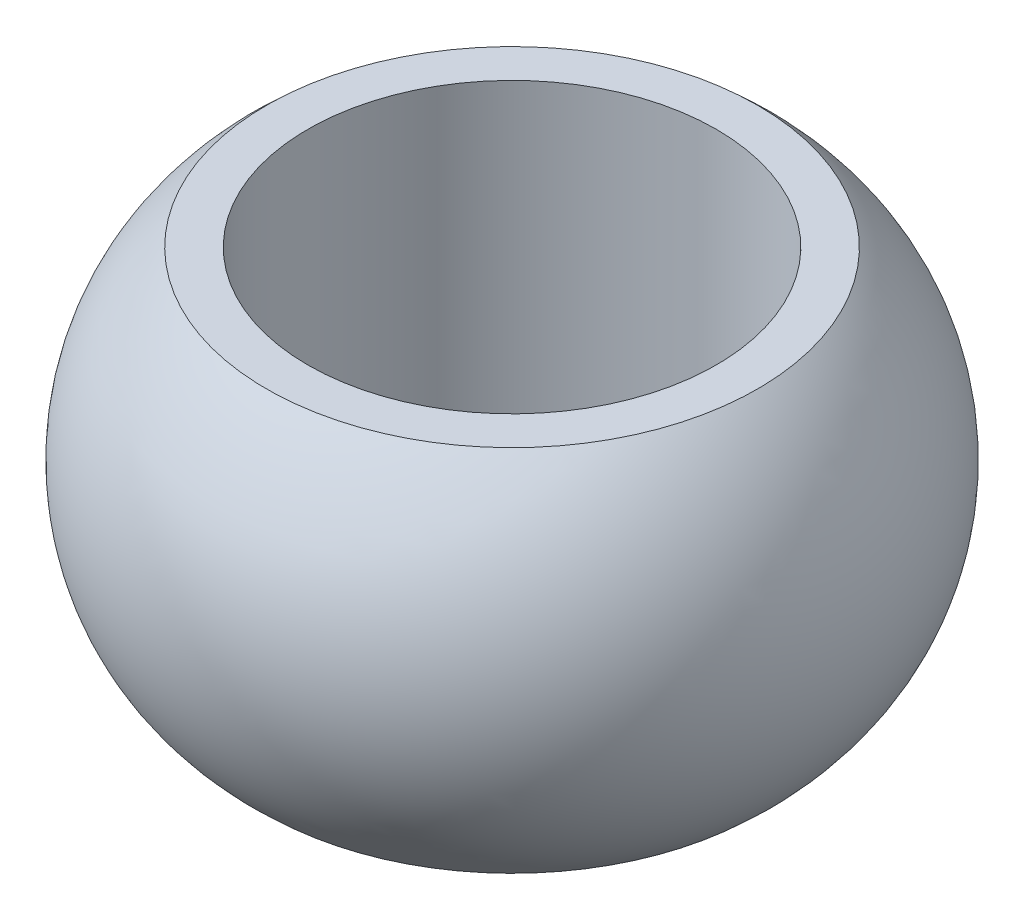
SolidWorks part; units mm, degrees
material "Chrome Stainless Steel"
ref_plane "Front Plane" through (0, 0, 0) normal (0, 0, 1) x (1, 0, 0)
ref_plane "Top Plane" through (0, 0, 0) normal (0, 1, 0) x (1, 0, 0)
ref_plane "Right Plane" through (0, 0, 0) normal (1, 0, 0) x (0, 0, -1)
sketch "Sketch1" plane through (0, 0, 0) normal (0, 0, 1) x (1, 0, 0)
  line L0 (0, 0) -> (0, 74.6658) construction
  line L1 (4.93, -4.45) -> (4.93, 4.45)
  line L2 (4.93, 4.45) -> (5.93, 4.45)
  line L3 (4.93, -4.45) -> (5.93, -4.45)
  arc A0 (5.93, 4.45) -> (5.93, -4.45) centre (2.0675, 0) cw
  point P8 (0, 0)
  point P9 (4.93, 0)
  dimension "D3" = 15.92
  dimension "D4" = 1
  dimension "D1" = 9.86
  dimension "D2" = 8.9
revolve "Revolve1" add sketch "Sketch1" angle 360 about L0
